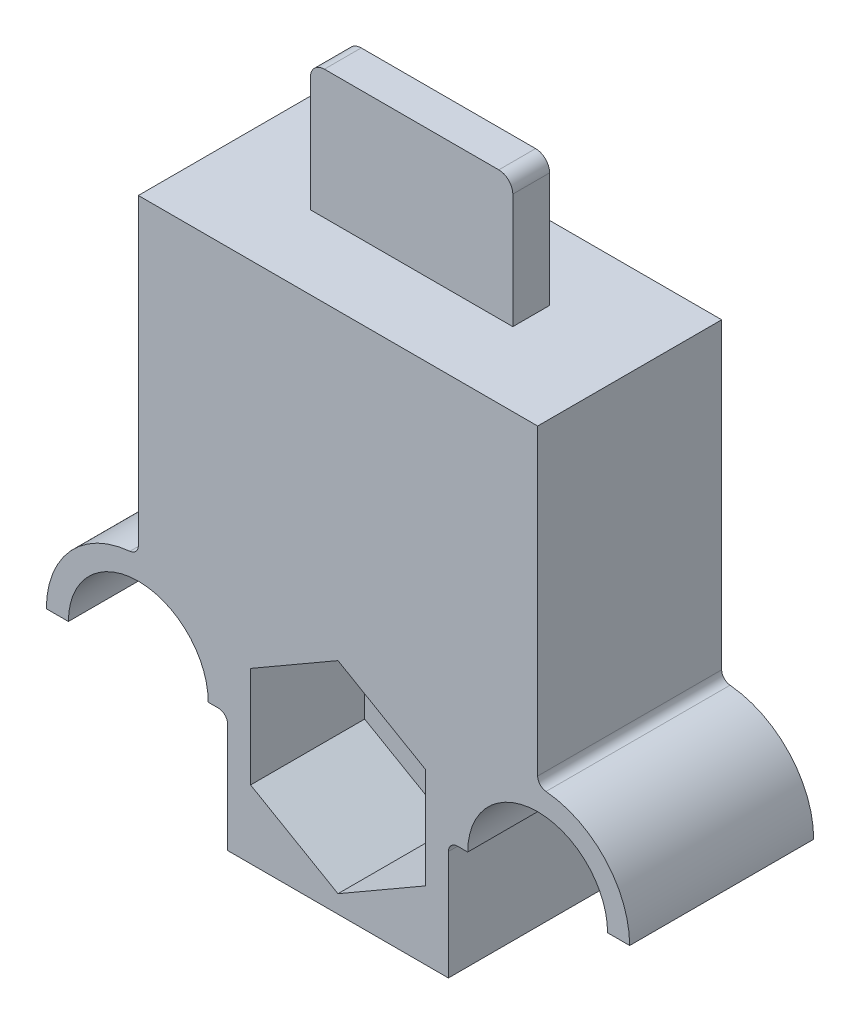
SolidWorks part; units mm, degrees
ref_plane "Front Plane" through (0, 0, 0) normal (0, 0, 1) x (1, 0, 0)
ref_plane "Top Plane" through (0, 0, 0) normal (0, 1, 0) x (1, 0, 0)
ref_plane "Right Plane" through (0, 0, 0) normal (1, 0, 0) x (0, 0, -1)
sketch "Sketch2" plane through (0, 0, -3838.4517) normal (0, 0, 1) x (1, 0, 0)
  line L0 (13.5, -20) -> (12.95, -20)
  line L1 (9.15, -14.5228) -> (9.15, 1.95)
  line L2 (9.15, 1.95) -> (30.85, 1.95)
  line L3 (30.85, 1.95) -> (30.85, -14.5228)
  line L4 (27.05, -20) -> (26.5, -20)
  line L9 (20, -26.4525) -> (14, -26.4525)
  line L10 (14, -26.4525) -> (14, -20.5)
  line L11 (20, -26.4525) -> (26, -26.4525)
  line L12 (26, -26.4525) -> (26, -20.5)
  line L14 (5.35, -20) -> (4.15, -20)
  line L15 (34.65, -20) -> (35.85, -20)
  arc A2 (8.6955, -15.0207) -> (4.15, -20) centre (9.15, -20) ccw
  arc A3 (35.85, -20) -> (31.3045, -15.0207) centre (30.85, -20) ccw
  arc A5 (12.95, -20) -> (5.35, -20) centre (9.15, -20) ccw
  arc A6 (34.65, -20) -> (27.05, -20) centre (30.85, -20) ccw
  arc A7 (31.3045, -15.0207) -> (30.85, -14.5228) centre (31.35, -14.5228) cw
  arc A8 (8.6955, -15.0207) -> (9.15, -14.5228) centre (8.65, -14.5228) ccw
  arc A9 (26.5, -20) -> (26, -20.5) centre (26.5, -20.5) ccw
  arc A10 (13.5, -20) -> (14, -20.5) centre (13.5, -20.5) cw
  circle A11 centre (20, -20) radius 2.5
  point P27 (14, -20)
  dimension "D1" = 3.8
  dimension "D2" = 3.8
  dimension "D6" = 10
  dimension "D3" = 0.5
  dimension "D4" = 6
  dimension "D5" = 6
extrude "Boss-Extrude1" add sketch "Sketch2" along normal blind 10
sketch "Sketch3" plane through (0, 0, -3828.4517) normal (0, 0, 1) x (1, 0, 0)
  line L1 (20, -25.4848) -> (24.75, -22.7424)
  line L2 (24.75, -22.7424) -> (24.75, -17.2576)
  line L3 (24.75, -17.2576) -> (20, -14.5152)
  line L4 (20, -14.5152) -> (15.25, -17.2576)
  line L5 (15.25, -17.2576) -> (15.25, -22.7424)
  line L6 (15.25, -22.7424) -> (20, -25.4848)
  circle A0 centre (20, -20) radius 4.75 construction
extrude "Cut-Extrude1" cut sketch "Sketch3" against normal blind 6.2
sketch "Sketch4" plane through (0, 1.95, 0) normal (0, 1, 0) x (1, 0, 0)
  line L0 (30.85, 3828.4517) -> (9.15, 3828.4517) construction
  line L1 (25.5, 3832.4517) -> (14.5, 3832.4517)
  line L2 (25.5, 3832.4517) -> (25.5, 3834.4517)
  line L3 (25.5, 3834.4517) -> (14.5, 3834.4517)
  line L4 (14.5, 3832.4517) -> (14.5, 3834.4517)
  line L5 (9.15, 3828.4517) -> (9.15, 3838.4517) construction
  dimension "D1" = 11
  dimension "D2" = 2
  dimension "D3" = 4
  dimension "D4" = 5.35
extrude "Boss-Extrude2" add sketch "Sketch4" along normal blind 7
fillet "Fillet1" radius 0.762 2 edges at (14.5, 8.95, -3833.4517) (25.5, 8.95, -3833.4517)
